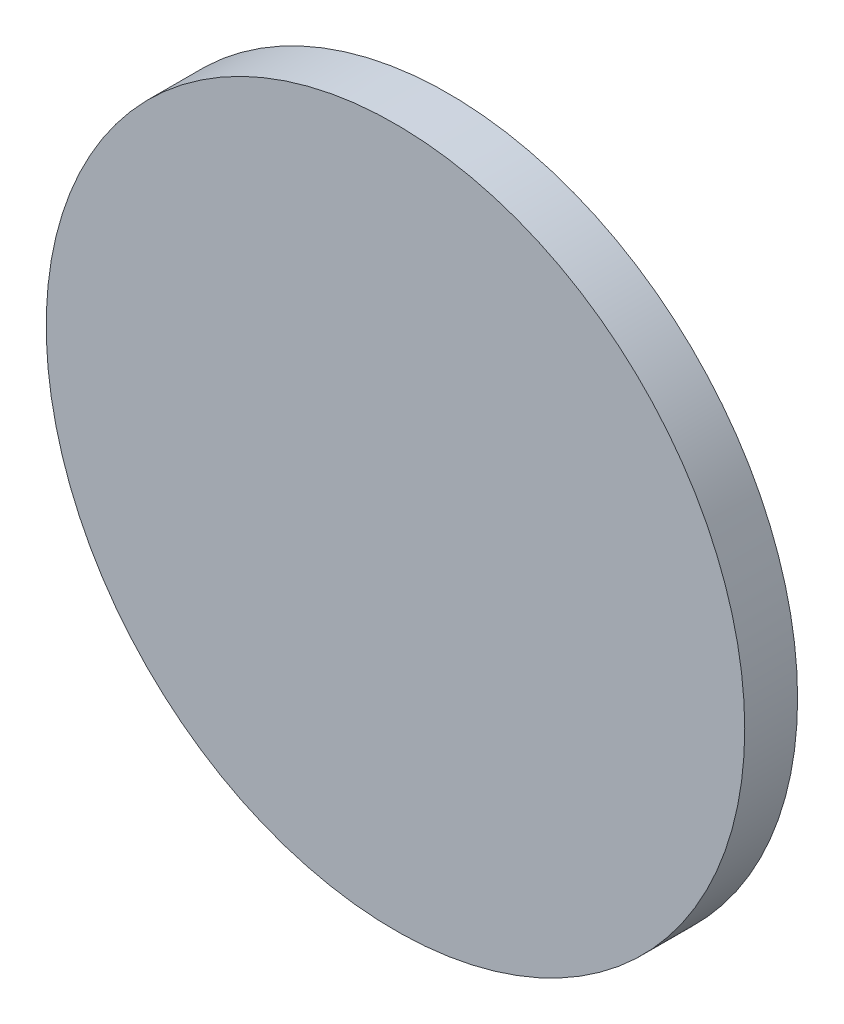
SolidWorks part; units mm, degrees
ref_plane "Front Plane" through (0, 0, 0) normal (0, 0, 1) x (1, 0, 0)
ref_plane "Top Plane" through (0, 0, 0) normal (0, 1, 0) x (1, 0, 0)
ref_plane "Right Plane" through (0, 0, 0) normal (1, 0, 0) x (0, 0, -1)
sketch "Sketch4" plane through (0, 0, 0) normal (0, 1, 0) x (1, 0, 0)
  line L0 (-11, 0) -> (0, 6.3509) construction
  line L1 (0, 6.3509) -> (11, 0) construction
  line L5 (0, 4.1509) -> (0, 0) construction
  line L7 (11, 0) -> (-11, 0) construction
  line L8 (-8.79, 1.2759) -> (0, 1.2759)
  line L9 (0, 4.1509) -> (0, 1.2759)
  spline S0 degree 2 poles (-8.79, 1.2759) (-4.894, 3.9693) (0, 4.1509) knots 0 0 0 1 1 1
  point P5 (0, 0)
  point P6 (0, 0)
  dimension "D2" = 2.2
  dimension "D4" = 22
  dimension "D1" = 120
  dimension "D5" = 8.79
revolve "Revolve1" add sketch "Sketch4" angle 360 about L9
sketch "Sketch5" plane through (0, 0, -1.2759) normal (0, 0, 1) x (1, 0, 0)
  circle A0 centre (0, 0) radius 8.79
extrude "Boss-Extrude3" add sketch "Sketch5" along normal blind 1.33
